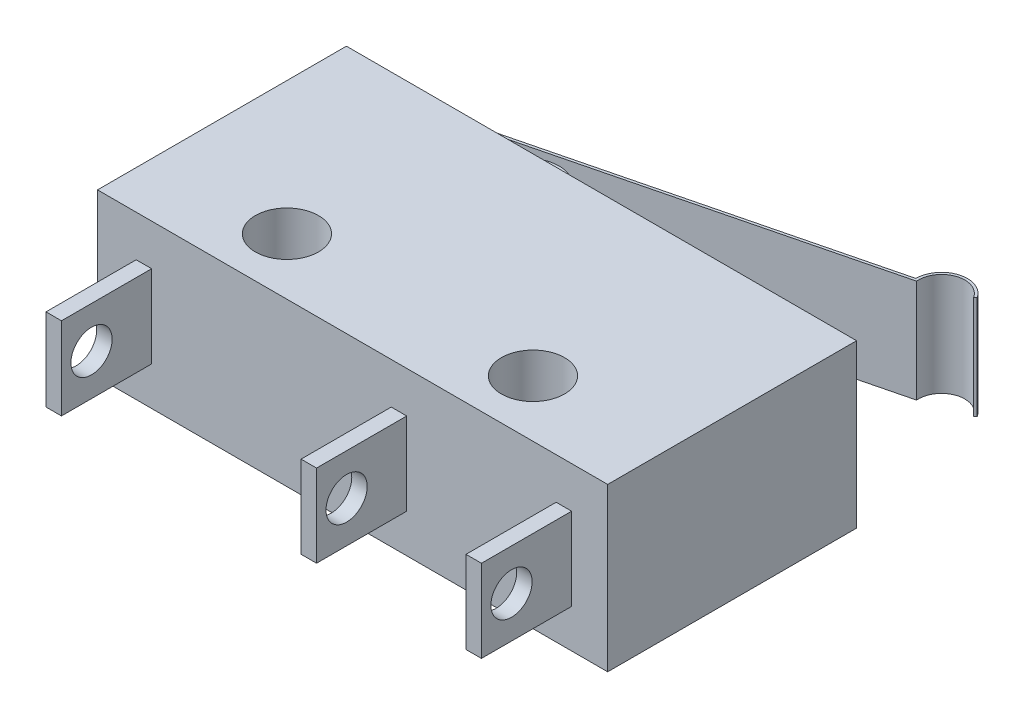
SolidWorks part; units mm, degrees
ref_plane "Front Plane" through (0, 0, 0) normal (0, 0, 1) x (1, 0, 0)
ref_plane "Top Plane" through (0, 0, 0) normal (0, 1, 0) x (1, 0, 0)
ref_plane "Right Plane" through (0, 0, 0) normal (1, 0, 0) x (0, 0, -1)
sketch "Sketch1" plane through (0, 0, 0) normal (0, 1, 0) x (1, 0, 0)
  line L1 (-9.9, 4.83) -> (9.9, 4.83)
  line L2 (-9.9, 4.83) -> (-9.9, -4.83)
  line L3 (-9.9, -4.83) -> (9.9, -4.83)
  line L4 (9.9, 4.83) -> (9.9, -4.83)
  line L5 (-9.9, 4.83) -> (9.9, -4.83) construction
  line L6 (-9.9, -4.83) -> (9.9, 4.83) construction
  point P0 (0, 0)
  dimension "D1" = 19.8
  dimension "D2" = 9.66
extrude "MainBody" add sketch "Sketch1" along normal blind 6.3
sketch "Sketch2" plane through (0, 6.3, 0) normal (0, 1, 0) x (1, 0, 0)
  line L0 (-9.9, -4.83) -> (9.9, -4.83) construction
  line L1 (9.9, -4.83) -> (9.9, 4.83) construction
  circle A0 centre (-4.75, -2.63) radius 1.225
  circle A1 centre (4.8, -2.63) radius 1.225
  dimension "D1" = 2.45
  dimension "D2" = 9.55
  dimension "D3" = 2.2
  dimension "D4" = 5.1
extrude "MountingHoles" cut sketch "Sketch2" against normal through all
sketch "Sketch3" plane through (0, 0, 4.83) normal (0, 0, 1) x (1, 0, 0)
  line L0 (-9.9, 0) -> (9.9, 0) construction
  line L1 (-8.4, 4.7) -> (-7.8, 4.7)
  line L2 (-8.4, 4.7) -> (-8.4, 1.5)
  line L3 (-8.4, 1.5) -> (-7.8, 1.5)
  line L4 (-7.8, 4.7) -> (-7.8, 1.5)
  line L5 (-9.9, 6.3) -> (-9.9, 0) construction
  line L6 (1.5, 4.7) -> (2.1, 4.7)
  line L7 (1.5, 4.7) -> (1.5, 1.5)
  line L8 (1.5, 1.5) -> (2.1, 1.5)
  line L9 (2.1, 4.7) -> (2.1, 1.5)
  line L10 (7.9, 4.7) -> (8.5, 4.7)
  line L11 (7.9, 4.7) -> (7.9, 1.5)
  line L12 (7.9, 1.5) -> (8.5, 1.5)
  line L13 (8.5, 4.7) -> (8.5, 1.5)
  dimension "D1" = 3.2
  dimension "D2" = 0.6
  dimension "D3" = 1.5
  dimension "D4" = 1.5
  dimension "D5" = 3.2
  dimension "D6" = 0.6
  dimension "D7" = 3.2
  dimension "D8" = 0.6
  dimension "D9" = 9.9
  dimension "D10" = 16.3
extrude "Boss-Extrude2" add sketch "Sketch3" along normal blind 3.5
sketch "Sketch4" plane through (8.5, 0, 0) normal (1, 0, 0) x (0, 0, -1)
  line L0 (-8.33, 4.7) -> (-4.83, 4.7) construction
  line L1 (-7.163, 4.7) -> (-7.163, 1.5) construction
  line L2 (-8.33, 1.5) -> (-4.83, 1.5) construction
  circle A0 centre (-7.163, 3.1) radius 0.8
  point P8 (-7.163, 3.1)
  dimension "D1" = 1.6
extrude "Cut-Extrude2" cut sketch "Sketch4" against normal through all
ref_plane "SwitchMidplane" through (0, 3.15, 0) normal (0, 1, 0) x (1, 0, 0)
sketch "Sketch5" plane through (0, 3.15, 0) normal (0, 1, 0) x (1, 0, 0)
  line L1 (-9.9, 4.83) -> (-9.9, -4.83) construction
  line L2 (9.9, 4.83) -> (-9.9, 4.83) construction
  circle A0 centre (-2.9, 4.83) radius 1.25
  dimension "D1" = 2.5
  dimension "D3" = 0
  dimension "D2" = 7
extrude "BumpSwitch" add sketch "Sketch5" along normal mid plane 4
sketch "Sketch6" plane through (0, 3.15, 0) normal (0, 1, 0) x (1, 0, 0)
  line L0 (-7.4086, 5.43) -> (7.8072, 9.2237)
  line L1 (9.9, 4.83) -> (-9.9, 4.83) construction
  line L2 (-9.9, 4.83) -> (-9.9, -4.83) construction
  line L3 (-7.9, 4.83) -> (-7.9, 4.2221)
  arc A0 (-7.4086, 5.43) -> (-7.9, 4.83) centre (-7.2516, 4.8002) ccw
  arc A1 (7.8072, 9.2237) -> (9.6472, 9.7641) centre (8.8072, 9.2215) cw
  dimension "D6" = 1
  dimension "D1" = 15.6816
  dimension "D2" = 0.6
  dimension "D3" = 2
  dimension "D4" = 14
  dimension "D5" = 2.4914
extrude "Extrude-Thin1" add sketch "Sketch6" along normal mid plane 4 thin
